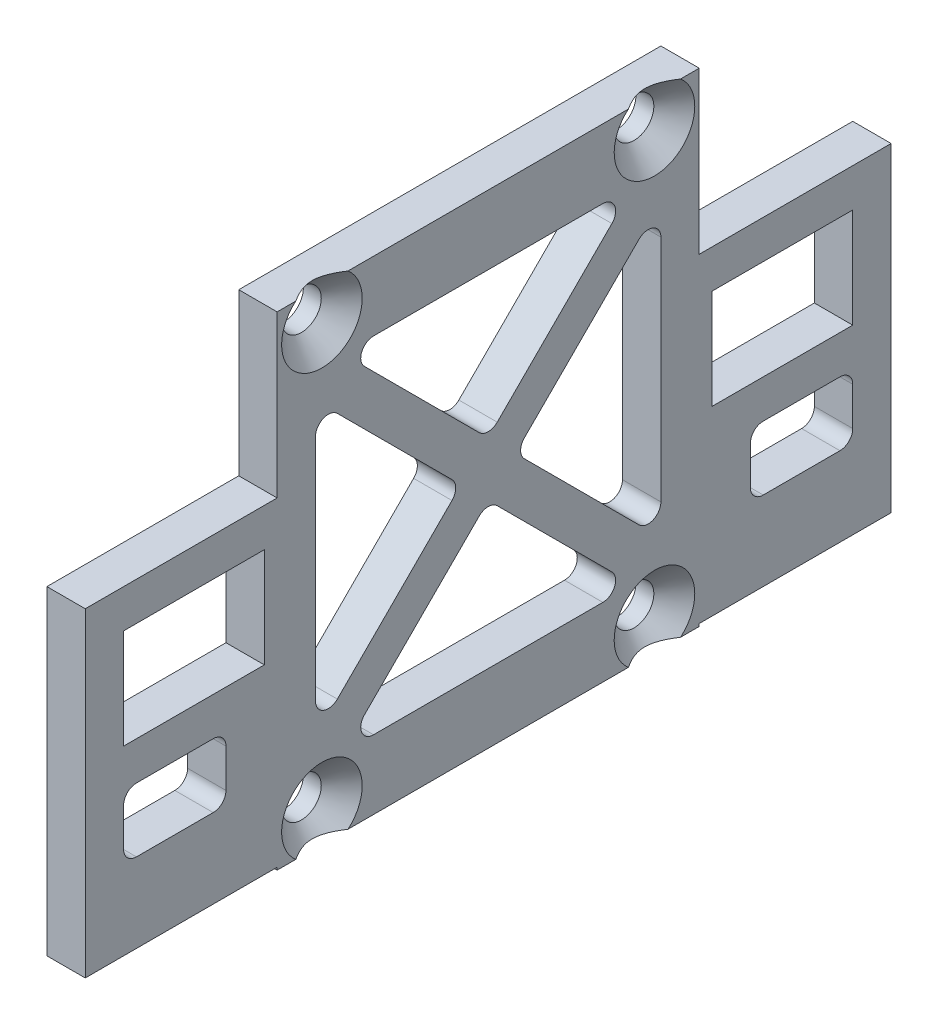
SolidWorks part; units mm, degrees
material "环氧树脂板"
ref_plane "前视基准面" through (0, 0, 0) normal (0, 0, 1) x (1, 0, 0)
ref_plane "上视基准面" through (0, 0, 0) normal (0, 1, 0) x (1, 0, 0)
ref_plane "右视基准面" through (0, 0, 0) normal (1, 0, 0) x (0, 0, -1)
sketch "草图1" plane through (0, 0, 0) normal (1, 0, 0) x (0, 0, -1)
  line L0 (0, 0) -> (10.3723, 0) construction
  line L1 (16.5, -18.9) -> (-16.5, -18.9)
  line L2 (16.5, -18.9) -> (16.5, -18.7)
  line L3 (16.5, 18.9) -> (-16.5, 18.9)
  line L4 (-16.5, -18.9) -> (-16.5, -18.7)
  line L5 (16.5, -18.9) -> (-16.5, 18.9) construction
  line L6 (16.5, 18.9) -> (-16.5, -18.9) construction
  line L7 (0, 0) -> (0, 11.3009) construction
  line L8 (28.5, -7.5) -> (20.5, -7.5)
  line L13 (-28.5, -12.5) -> (-20.5, -12.5)
  line L14 (-28.5, -12.5) -> (-28.5, -7.5)
  line L19 (-28.5, -7.5) -> (-20.5, -7.5)
  line L20 (-20.5, -12.5) -> (-20.5, -7.5)
  line L21 (-28.5, -12.5) -> (-20.5, -7.5) construction
  line L22 (-28.5, -7.5) -> (-20.5, -12.5) construction
  line L23 (20.5, -12.5) -> (20.5, -7.5)
  line L24 (28.5, -12.5) -> (20.5, -12.5)
  line L25 (28.5, -12.5) -> (28.5, -7.5)
  line L26 (24.5, -7.5) -> (24.5, -13.4628) construction
  line L27 (-31.5, -18.7) -> (-16.5, -18.7)
  line L28 (-31.5, -18.7) -> (-31.5, 6.3)
  line L29 (-31.5, 6.3) -> (-16.5, 6.3)
  line L30 (31.5, -18.7) -> (16.5, -18.7)
  line L31 (31.5, -18.7) -> (31.5, 6.3)
  line L32 (31.5, 6.3) -> (16.5, 6.3)
  line L33 (-16.5, 6.3) -> (-16.5, 18.9)
  line L34 (16.5, 6.3) -> (16.5, 18.9)
  line L35 (-13.5, -11.3787) -> (-2.1213, 0)
  line L36 (13.5, -13.5) -> (-13.5, -13.5) construction
  line L37 (13.5, -13.5) -> (13.5, 13.5) construction
  line L38 (13.5, 13.5) -> (-13.5, 13.5) construction
  line L39 (-13.5, -13.5) -> (-13.5, 13.5) construction
  line L40 (13.5, -13.5) -> (-13.5, 13.5) construction
  line L41 (13.5, 13.5) -> (-13.5, -13.5) construction
  line L42 (-11.3787, -13.5) -> (0, -2.1213)
  line L43 (-11.3787, 13.5) -> (0, 2.1213)
  line L44 (-13.5, 11.3787) -> (-2.1213, 0)
  line L45 (-11.3787, 13.5) -> (11.3787, 13.5)
  line L46 (13.5, 11.3787) -> (13.5, -11.3787)
  line L47 (11.3787, -13.5) -> (-11.3787, -13.5)
  line L48 (-13.5, 11.3787) -> (-13.5, -11.3787)
  line L49 (0, 2.1213) -> (11.3787, 13.5)
  line L50 (2.1213, 0) -> (13.5, -11.3787)
  line L51 (2.1213, 0) -> (13.5, 11.3787)
  line L52 (0, -2.1213) -> (11.3787, -13.5)
  line L53 (17.5, 3.3) -> (28.5, 3.3)
  line L54 (-17.5, -4.5) -> (-28.5, -4.5)
  line L55 (-17.5, -4.5) -> (-17.5, 3.3)
  line L56 (-17.5, 3.3) -> (-28.5, 3.3)
  line L57 (-28.5, -4.5) -> (-28.5, 3.3)
  line L58 (-17.5, -4.5) -> (-28.5, 3.3) construction
  line L59 (-17.5, 3.3) -> (-28.5, -4.5) construction
  line L60 (28.5, -4.5) -> (28.5, 3.3)
  line L61 (17.5, -4.5) -> (28.5, -4.5)
  line L62 (17.5, -4.5) -> (17.5, 3.3)
  circle A0 centre (-13, 16.5) radius 1.55
  circle A1 centre (-13, -16.5) radius 1.55
  circle A2 centre (13, -16.5) radius 1.55
  circle A3 centre (13, 16.5) radius 1.55
  point P0 (0, 0)
  point P17 (-24.5, -10)
  point P53 (-23, -0.6)
  dimension "D5" = 3.1
  dimension "D1" = 26
  dimension "D2" = 33
  dimension "D3" = 2.4
  dimension "D4" = 3.5
  dimension "D6" = 49
  dimension "D7" = 8
  dimension "D8" = 5
  dimension "D9" = 12.5
  dimension "D10" = 0.2
  dimension "D11" = 25
  dimension "D12" = 3
  dimension "D13" = 3
  dimension "D14" = 4
  dimension "D15" = 3
  dimension "D16" = 3
  dimension "D17" = 3
  dimension "D18" = 3
extrude "凸台-拉伸1" add sketch "草图1" along normal blind 3
hole_wizard "M3 锥坑高头螺钉的锥形沉头孔1" positions "3D草图1" profile "草图2" countersink size "M3" standard "ISO" end condition through all
sketch3d "3D草图1"
  line L0 (3, 16.5, 13) -> (0, 16.5, 13) construction
  line L1 (3, 16.5, -13) -> (0, 16.5, -13) construction
  line L2 (3, -16.5, -13) -> (0, -16.5, -13) construction
  line L3 (3, -16.5, 13) -> (0, -16.5, 13) construction
  point P0 (3, 16.5, 13)
  point P4 (3, 16.5, -13)
  point P8 (3, -16.5, -13)
  point P12 (3, -16.5, 13)
sketch "草图2" plane through (3, 16.5, 13) normal (0, 1, 0) x (0, 0, -1)
  line L0 (0, 0) -> (0, 3)
  line L1 (0, 3) -> (1.55, 3)
  line L2 (1.55, 3) -> (1.55, 1.6)
  line L3 (1.55, 1.6) -> (3.15, 0)
  line L5 (3.15, 0) -> (0, 0)
  line L6 (-1.55, 1.6) -> (-3.15, 0) construction
  line L11 (0, -6.35) -> (0, 107.95) construction
  dimension "通孔孔直径" = 3.1
  dimension "通孔孔深度" = 3
  dimension "近端锥形沉头孔直径" = 6.3
  dimension "近端锥形沉头孔角度" = 90
fillet "圆角1" radius 1 20 edges at (1.5, -11.3787, -13.5) (1.5, 11.3787, -13.5) (1.5, 0, -2.1213) (1.5, -2.1213, 0) (1.5, -13.5, 11.3787) (1.5, -13.5, -11.3787) (1.5, 13.5, 11.3787) (1.5, 2.1213, 0) (1.5, 13.5, -11.3787) (1.5, 0, 2.1213) (1.5, -11.3787, 13.5) (1.5, -7.5, -20.5) (1.5, -12.5, -20.5) (1.5, -12.5, -28.5) (1.5, -7.5, -28.5) (1.5, -7.5, 28.5) (1.5, -12.5, 28.5) (1.5, -12.5, 20.5) (1.5, -7.5, 20.5) (1.5, 11.3787, 13.5)
